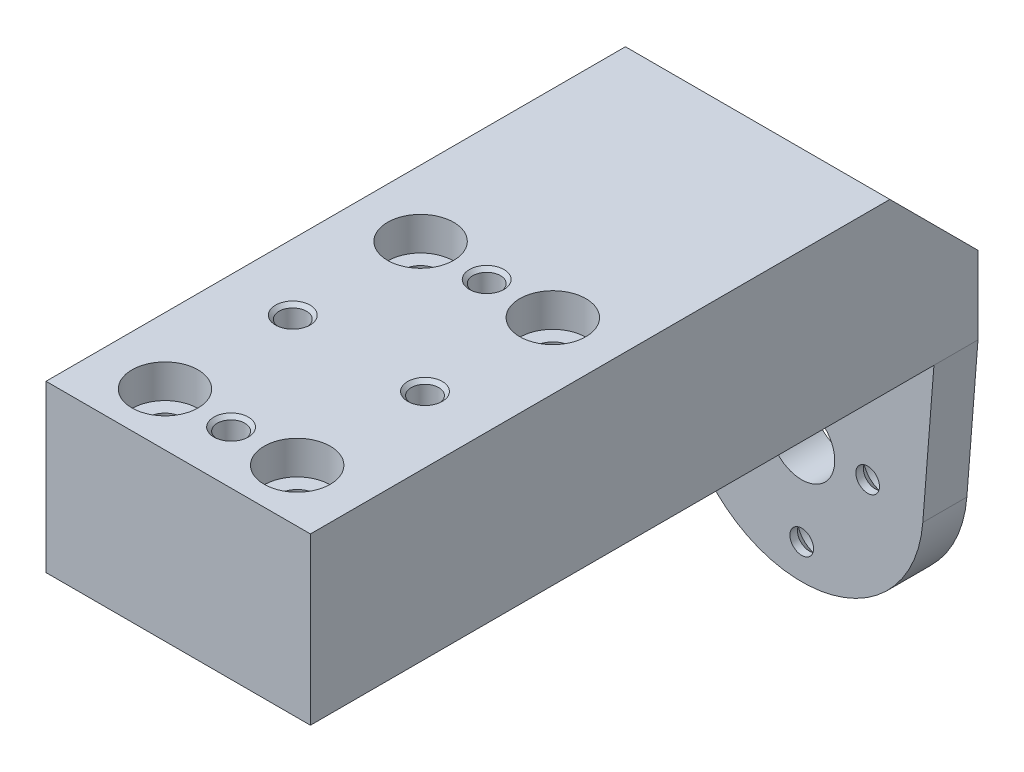
SolidWorks part; units mm, degrees
material "ABS"
ref_plane "Front Plane" through (0, 0, 0) normal (0, 0, 1) x (1, 0, 0)
ref_plane "Top Plane" through (0, 0, 0) normal (0, 1, 0) x (1, 0, 0)
ref_plane "Right Plane" through (0, 0, 0) normal (1, 0, 0) x (0, 0, -1)
sketch "Sketch1" plane through (0, 0, 0) normal (0, 0, 1) x (1, 0, 0)
  line L1 (-19.05, -11.938) -> (19.05, -11.938)
  line L2 (-19.05, -11.938) -> (-19.05, 11.938)
  line L3 (-19.05, 11.938) -> (19.05, 11.938)
  line L4 (19.05, -11.938) -> (19.05, 11.938)
  line L5 (-19.05, -11.938) -> (19.05, 11.938) construction
  line L6 (-19.05, 11.938) -> (19.05, -11.938) construction
  point P0 (0, 0)
  dimension "D1" = 23.876
  dimension "D2" = 38.1
extrude "Gearbox Mount" add sketch "Sketch1" along normal blind 48.26
sketch "Gearbox Hole Pattern" plane through (0, 11.938, 0) normal (0, 1, 0) x (1, 0, 0)
  line L1 (9.525, -40.64) -> (-9.525, -40.64) construction
  line L2 (9.525, -40.64) -> (9.525, -3.81) construction
  line L3 (9.525, -3.81) -> (-9.525, -3.81) construction
  line L4 (-9.525, -40.64) -> (-9.525, -3.81) construction
  line L5 (9.525, -40.64) -> (-9.525, -3.81) construction
  line L6 (9.525, -3.81) -> (-9.525, -40.64) construction
  line L7 (19.05, -48.26) -> (19.05, 0) construction
  line L8 (19.05, -48.26) -> (-19.05, -48.26) construction
  point P0 (0, -22.225)
  dimension "D1" = 19.05
  dimension "D2" = 36.83
  dimension "D3" = 44.45
  dimension "D4" = 19.05
hole_wizard "CBORE for #4 Socket Head Cap Screw1" positions "Sketch6" profile "Sketch5" counterbore size "#4" standard "ANSI Inch"
sketch "Sketch6" plane through (0, 11.938, 0) normal (0, 1, 0) x (1, 0, 0)
  line L0 (9.525, -3.81) -> (-9.525, -3.81) construction
  line L1 (-9.525, -40.64) -> (-9.525, -3.81) construction
  line L2 (9.525, -40.64) -> (-9.525, -40.64) construction
  line L3 (9.525, -40.64) -> (9.525, -3.81) construction
  point P0 (0, -3.81)
  point P4 (-9.525, -22.225)
  point P8 (0, -40.64)
  point P12 (9.525, -22.225)
sketch "Sketch5" plane through (0, 11.938, 3.81) normal (1, 0, 0) x (0, 0, 1)
  line L0 (0, 0) -> (0, 13.6806)
  line L1 (0, 13.6806) -> (1.6319, 12.7)
  line L2 (1.6319, 12.7) -> (1.6319, 4.7625)
  line L3 (1.6319, 4.7625) -> (1.9844, 4.7625)
  line L4 (1.9844, 4.7625) -> (1.9844, 0)
  line L5 (1.9844, 0) -> (0, 0)
  line L10 (0, 13.6806) -> (-1.632, 12.7) construction
  line L11 (0, -6.35) -> (0, 107.95) construction
  dimension "Hole Dia." = 3.2639
  dimension "Hole Depth" = 12.7
  dimension "C'Bore Dia." = 3.9688
  dimension "C'Bore Depth" = 4.7625
  dimension "Drill Angle" = 118
chamfer "Insert Installation Chamfers" distance 0.508 angle 45 4 edges at (0, 11.938, 42.6244) (9.525, 11.938, 24.2094) (0, 11.938, 5.7944) (-9.525, 11.938, 24.2094)
sketch "Sketch7" plane through (0, 0, 0) normal (0, 0, -1) x (-1, 0, 0)
  line L1 (-19.05, -11.938) -> (19.05, -11.938)
  line L2 (-19.05, -11.938) -> (-19.05, 11.938)
  line L3 (-19.05, 11.938) -> (19.05, 11.938)
  line L4 (19.05, -11.938) -> (19.05, 11.938)
  line L5 (-19.05, -11.938) -> (19.05, 11.938) construction
  line L6 (-19.05, 11.938) -> (19.05, -11.938) construction
  point P0 (0, 0)
extrude "Motor Mount Extension" add sketch "Sketch7" along normal blind 41.5798
hole_wizard "CBORE for #10 Socket Head Cap Screw1" positions "Sketch4" profile "Sketch3" counterbore size "#10" standard "ANSI Inch" end condition through all
sketch "Sketch4" plane through (0, 11.938, 0) normal (0, 1, 0) x (1, 0, 0)
  point P0 (-9.525, -40.64)
  point P3 (9.525, -40.64)
  point P7 (9.525, -3.81)
  point P10 (-9.525, -3.81)
sketch "Sketch3" plane through (-9.525, 11.938, 40.64) normal (1, 0, 0) x (0, 0, 1)
  line L0 (0, 0) -> (0, 23.876)
  line L1 (0, 23.876) -> (2.5527, 23.876)
  line L3 (2.5527, 23.876) -> (2.5527, 4.826)
  line L4 (2.5527, 4.826) -> (4.7625, 4.826)
  line L5 (4.7625, 4.826) -> (4.7625, 0)
  line L7 (4.7625, 0) -> (0, 0)
  line L11 (0, -6.35) -> (0, 107.95) construction
  dimension "Thru Hole Dia." = 5.1054
  dimension "Thru Hole Depth" = 23.876
  dimension "C'Bore Dia." = 9.525
  dimension "C'Bore Depth" = 4.826
sketch "Sketch8" plane through (0, 0, -41.5798) normal (0, 0, -1) x (-1, 0, 0)
  line L0 (19.05, 11.938) -> (-19.05, 11.938)
  line L1 (-19.05, 11.938) -> (-19.05, -11.938) construction
  line L2 (19.05, 11.938) -> (-19.05, 11.938) construction
  line L3 (-19.05, 11.938) -> (-19.05, -11.938)
  line L4 (19.05, 11.938) -> (19.05, -11.938)
  line L5 (-19.05, -11.938) -> (19.05, -11.938) construction
  line L6 (-19.05, -11.938) -> (-17.4463, -32.3582)
  line L7 (19.05, -11.938) -> (17.4463, -32.3582)
  line L8 (0, 0) -> (0, -30.988) construction
  arc A0 (-17.4463, -32.3582) -> (17.4463, -32.3582) centre (0, -30.988) ccw
  dimension "D2" = 17.5
  dimension "D1" = 19.05
extrude "Motor Mount Plate" add sketch "Sketch8" along normal blind 6.35
sketch "Sketch9" plane through (0, 0, -47.9298) normal (0, 0, -1) x (-1, 0, 0)
  circle A0 centre (0, -30.988) radius 4.7625
  arc A1 (-17.4463, -32.3582) -> (17.4463, -32.3582) centre (0, -30.988) ccw construction
  dimension "D1" = 9.525
extrude "Shaft Clearance" cut sketch "Sketch9" against normal up to next
hole_wizard "CSK for M3 Flat Head Machine Screw1" positions "Sketch11" profile "Sketch10" countersink size "M3" standard "ANSI Metric" end condition up to next
sketch "Sketch11" plane through (0, 0, -47.9298) normal (0, 0, -1) x (-1, 0, 0)
  circle A0 centre (0, -30.988) radius 9.5 construction
  circle A1 centre (0, -30.988) radius 12.5 construction
  circle A3 centre (0, -30.988) radius 4.7625 construction
  point P9 (-9.5, -30.988)
  point P11 (9.5, -30.988)
  point P13 (0, -18.488)
  point P15 (0, -43.488)
  dimension "D1" = 25
  dimension "D2" = 19
sketch "Sketch10" plane through (9.5, -30.988, -47.9298) normal (1, 0, 0) x (0, 1, 0)
  line L0 (0, 0) -> (0, 6.35)
  line L1 (0, 6.35) -> (1.7, 6.35)
  line L2 (1.7, 6.35) -> (1.7, 5.26)
  line L3 (1.7, 5.26) -> (3.15, 3.81)
  line L4 (3.15, 3.81) -> (3.15, 0)
  line L6 (3.15, 0) -> (0, 0)
  line L7 (-1.7, 5.26) -> (-3.15, 3.81) construction
  line L11 (0, -6.35) -> (0, 107.95) construction
  dimension "Thru Hole Dia." = 3.4
  dimension "Thru Hole Depth" = 6.35
  dimension "C'Sink Dia." = 6.3
  dimension "C'Sink Angle" = 90
  dimension "Head Clearance" = 3.81
chamfer "Chamfer2" distance 12.7 angle 45 1 edges at (0, 11.938, -47.9298)
